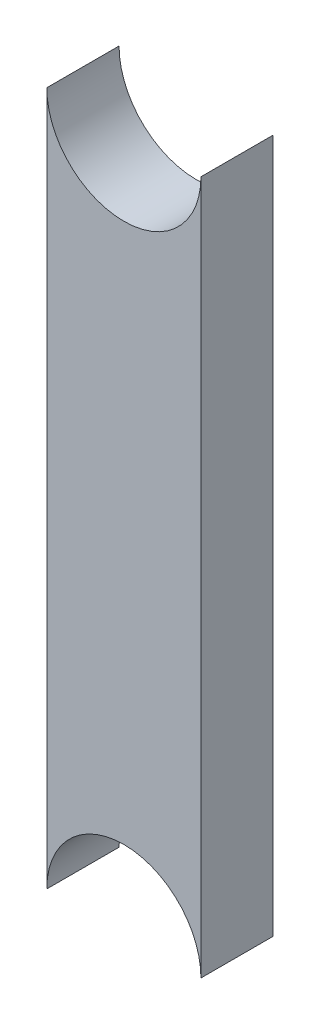
SolidWorks part; units mm, degrees
ref_plane "Front Plane" through (0, 0, 0) normal (0, 0, 1) x (1, 0, 0)
ref_plane "Top Plane" through (0, 0, 0) normal (0, 1, 0) x (1, 0, 0)
ref_plane "Right Plane" through (0, 0, 0) normal (1, 0, 0) x (0, 0, -1)
sketch "Sketch1" plane through (0, 0, 0) normal (0, 0, 1) x (1, 0, 0)
  line L1 (-3.2, 0) -> (-3.2, 28.8)
  line L2 (3.2, 28.8) -> (3.2, 0)
  line L3 (0, -2.75) -> (0, 2.75) construction
  arc A2 (3.2, 0) -> (-3.2, 0) centre (0, 0) ccw
  arc A3 (-3.2, 28.8) -> (3.2, 28.8) centre (0, 28.8) ccw
  dimension "D1" = 6.4
  dimension "D2" = 28.8
extrude "Boss-Extrude3" add sketch "Sketch1" along normal blind 3
equation "\"bScale\"= 8"
equation "\"lScale\"= 8"
equation "\"D1@Sketch1\"=.8*\"bScale\""
equation "\"D2@Sketch1\"=3.6*\"lScale\""
